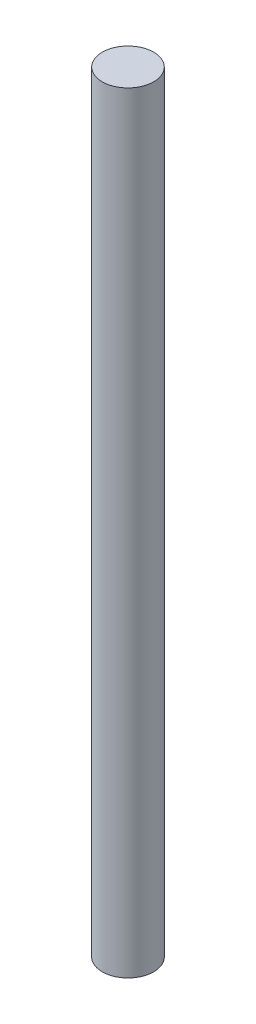
SolidWorks part; units mm, degrees
ref_plane "前视基准面" through (0, 0, 0) normal (0, 0, 1) x (1, 0, 0)
ref_plane "上视基准面" through (0, 0, 0) normal (0, 1, 0) x (1, 0, 0)
ref_plane "右视基准面" through (0, 0, 0) normal (1, 0, 0) x (0, 0, -1)
other "Configuration Table"
sketch "草图1" plane through (0, 0, 0) normal (0, 1, 0) x (1, 0, 0)
  circle A0 centre (0, 0) radius 5
  dimension "D1" = 10
extrude "凸台-拉伸2" add sketch "草图1" along normal blind 150
